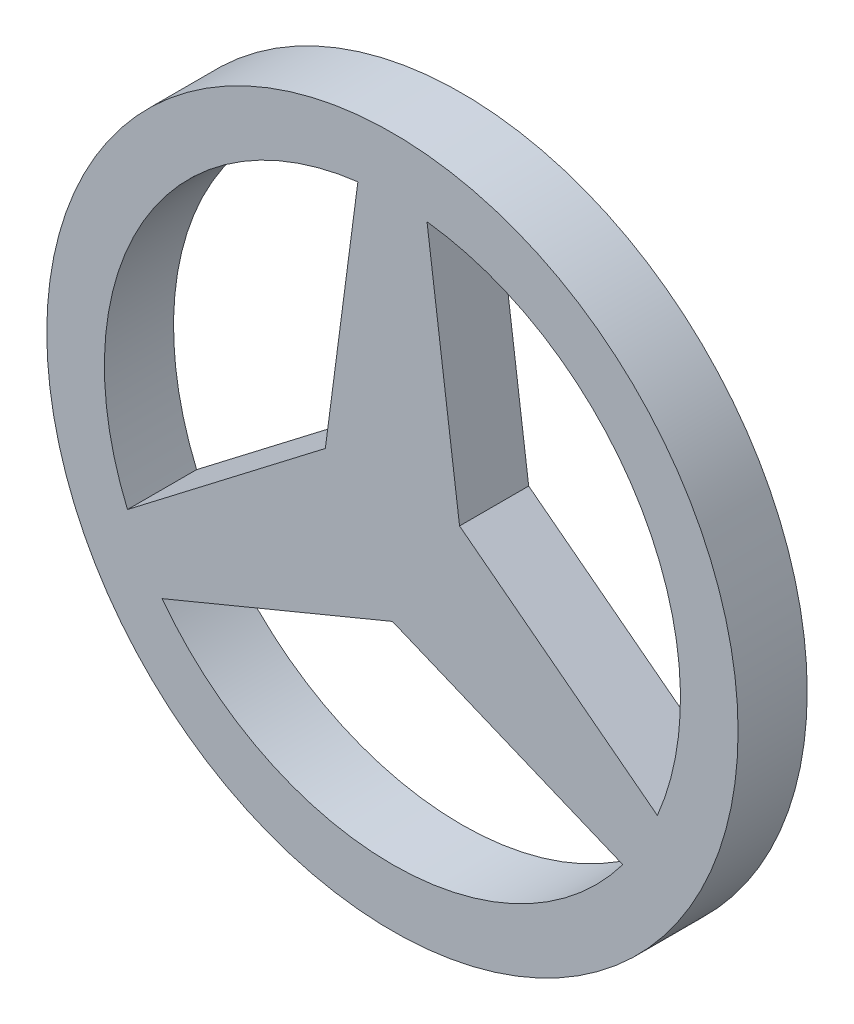
SolidWorks part; units mm, degrees
ref_plane "前视基准面" through (0, 0, 0) normal (0, 0, 1) x (1, 0, 0)
ref_plane "上视基准面" through (0, 0, 0) normal (0, 1, 0) x (1, 0, 0)
ref_plane "右视基准面" through (0, 0, 0) normal (1, 0, 0) x (0, 0, -1)
sketch "草图1" plane through (0, 0, 0) normal (0, 0, 1) x (1, 0, 0)
  line L0 (-1.5, 12.4097) -> (-2.9124, 1.6815)
  line L1 (-2.9124, 1.6815) -> (-11.4971, -4.9058)
  line L2 (1.5, 12.4097) -> (2.9124, 1.6815)
  line L3 (2.9124, 1.6815) -> (11.4971, -4.9058)
  line L4 (9.9971, -7.5039) -> (0, -3.3629)
  line L5 (0, -3.3629) -> (-9.9971, -7.5039)
  line L6 (0, 0) -> (0, 12.5) construction
  line L7 (0, 0) -> (-10.8253, -6.25) construction
  line L8 (0, 0) -> (10.8253, -6.25) construction
  circle A0 centre (0, 0) radius 15
  circle A1 centre (0, 0) radius 12.5
  circle A2 centre (0, 0) radius 3.3629 construction
  dimension "D5" = 25
  dimension "D6" = 30
  dimension "D1" = 15
  dimension "D2" = 15
  dimension "D3" = 15
  dimension "D4" = 3
  dimension "D7" = 120
  dimension "D8" = 120
  dimension "D9" = 7.5
  dimension "D10" = 3
extrude "凸台-拉伸1" add sketch "草图1" along normal blind 3 contours L2 A1 L0 L1 L5 L4 L3 | A0 A1
